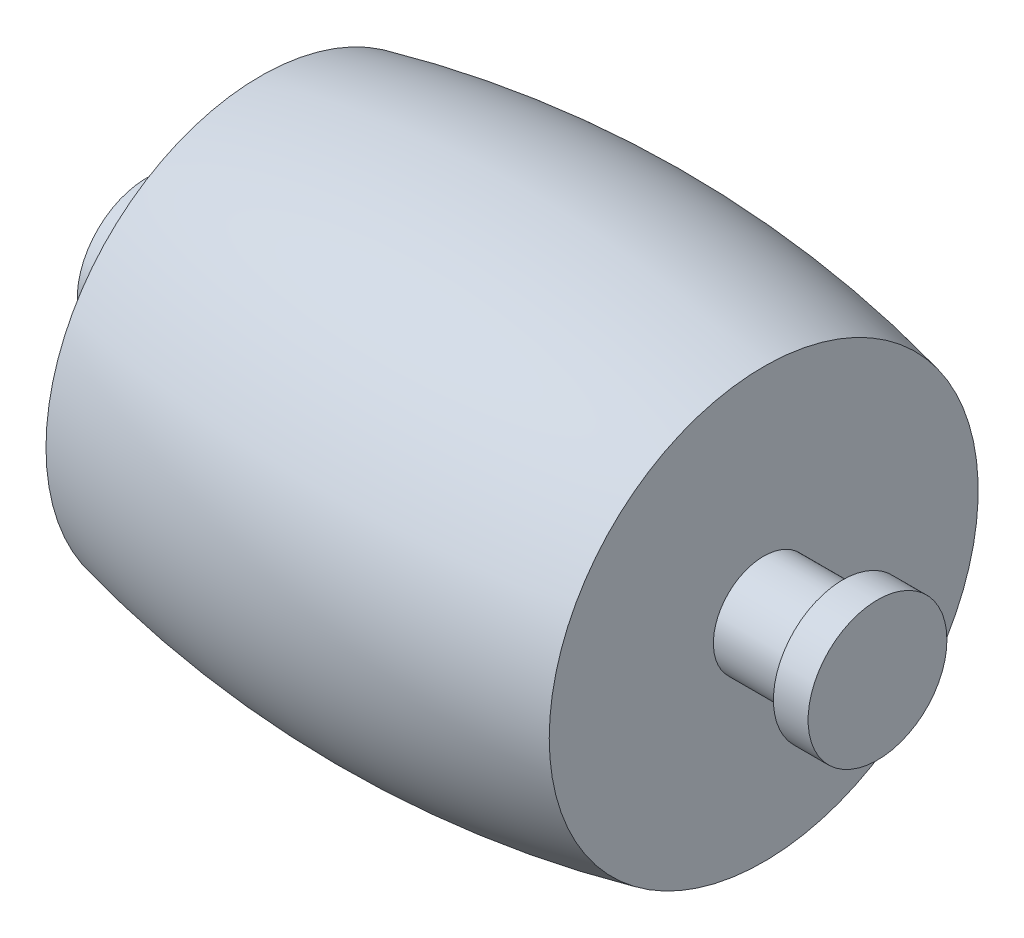
SolidWorks part; units mm, degrees
ref_plane "Front Plane" through (0, 0, 0) normal (0, 0, 1) x (1, 0, 0)
ref_plane "Top Plane" through (0, 0, 0) normal (0, 1, 0) x (1, 0, 0)
ref_plane "Right Plane" through (0, 0, 0) normal (1, 0, 0) x (0, 0, -1)
sketch "Sketch2" plane through (0, 0, 0) normal (0, 0, 1) x (1, 0, 0)
  line L0 (-18.415, 0) -> (18.415, 0) construction
  line L1 (0, 0) -> (0, 17.78) construction
  line L2 (-18.415, 0) -> (-18.415, 15.6976)
  line L3 (18.415, 0) -> (18.415, 15.6976)
  line L4 (0, 17.78) -> (0, -64.6836) construction
  line L6 (-18.415, 0) -> (18.415, 0)
  arc A0 (0, 17.78) -> (18.415, 15.6976) centre (0, -64.6836) cw
  arc A1 (0, 17.78) -> (-18.415, 15.6976) centre (0, -64.6836) ccw
  point P4 (0, 0)
  point P10 (0, 17.78)
  dimension "D1" = 36.83
  dimension "D2" = 17.78
  dimension "D3" = 82.4636
revolve "Revolve1" add sketch "Sketch2" angle 360 about L6
sketch "Sketch4" plane through (18.415, 0, 0) normal (1, 0, 0) x (0, 0, -1)
  circle A0 centre (0, 0) radius 3.683
  dimension "D1" = 7.366
extrude "Boss-Extrude1" add sketch "Sketch4" along normal blind 5.789
sketch "Sketch5" plane through (24.204, 0, 0) normal (1, 0, 0) x (0, 0, -1)
  circle A0 centre (0, 0) radius 5.08
  dimension "D1" = 10.16
extrude "Boss-Extrude2" add sketch "Sketch5" along normal blind 2.54
mirror "Mirror1" about plane through (0, 0, 0) normal (1, 0, 0) of "Boss-Extrude1", "Boss-Extrude2"
